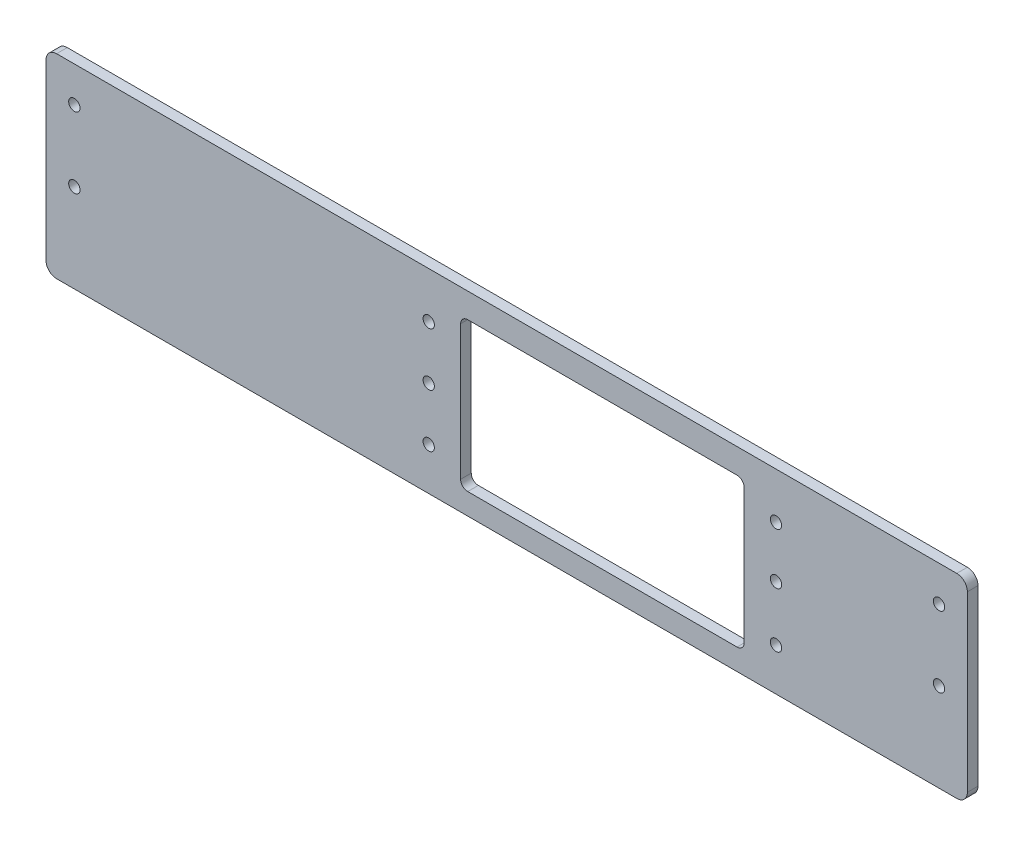
SolidWorks part; units mm, degrees
material "Thornel Mat VMA"
ref_plane "前视基准面" through (0, 0, 0) normal (0, 0, 1) x (1, 0, 0)
ref_plane "上视基准面" through (0, 0, 0) normal (0, 1, 0) x (1, 0, 0)
ref_plane "右视基准面" through (0, 0, 0) normal (1, 0, 0) x (0, 0, -1)
other "Configuration Table"
sketch "草图1" plane through (0, 0, 0) normal (0, 0, 1) x (1, 0, 0)
  line L1 (130, -27.5) -> (-130, -27.5)
  line L2 (130, -27.5) -> (130, 27.5)
  line L3 (130, 27.5) -> (-130, 27.5)
  line L4 (-130, -27.5) -> (-130, 27.5)
  line L5 (130, -27.5) -> (-130, 27.5) construction
  line L6 (130, 27.5) -> (-130, -27.5) construction
  point P0 (0, 0)
  dimension "D1" = 260
  dimension "D2" = 55
extrude "凸台-拉伸1" add sketch "草图1" along normal blind 3
fillet "圆角1" radius 3 4 edges at (130, 27.5, 1.5) (130, -27.5, 1.5) (-130, -27.5, 1.5) (-130, 27.5, 1.5)
sketch "草图2" plane through (0, 0, 3) normal (0, 0, 1) x (1, 0, 0)
  line L0 (-122, 27.5) -> (-122, -27.5) construction
  line L1 (127, 27.5) -> (-127, 27.5) construction
  line L2 (-127, -27.5) -> (127, -27.5) construction
  line L3 (122, 27.5) -> (122, -27.5) construction
  line L4 (130, -24.5) -> (130, 24.5) construction
  line L5 (-130, 24.5) -> (-130, -24.5) construction
  line L6 (0, 27.5) -> (0, -27.5) construction
  circle A0 centre (-122, 17.5) radius 1.6
  circle A1 centre (-122, -2.5) radius 1.6
  circle A2 centre (122, -2.5) radius 1.6
  circle A3 centre (122, 17.5) radius 1.6
  dimension "D3" = 20
  dimension "D4" = 10
  dimension "D5" = 3.2
  dimension "D1" = 8
  dimension "D2" = 8
extrude "切除-拉伸1" cut sketch "草图2" against normal blind 48
sketch "草图3" plane through (0, 0, 3) normal (0, 0, 1) x (1, 0, 0)
  line L0 (127, 27.5) -> (-127, 27.5) construction
  line L1 (-13, 20.5) -> (67, 20.5)
  line L2 (-13, 20.5) -> (-13, -21.5)
  line L3 (-13, -21.5) -> (67, -21.5)
  line L4 (67, 20.5) -> (67, -21.5)
  line L6 (130, -24.5) -> (130, 24.5) construction
  line L7 (27, 20.5) -> (27, -21.5) construction
  line L9 (76, -15.5) -> (-22, -15.5) construction
  line L10 (76, -15.5) -> (76, 14.5) construction
  line L11 (76, 14.5) -> (-22, 14.5) construction
  line L12 (-22, -15.5) -> (-22, 14.5) construction
  line L13 (76, -15.5) -> (-22, 14.5) construction
  line L14 (76, 14.5) -> (-22, -15.5) construction
  circle A0 centre (-22, 14.5) radius 1.6
  circle A1 centre (-22, -0.5) radius 1.6
  circle A2 centre (-22, -15.5) radius 1.6
  circle A3 centre (76, 14.5) radius 1.6
  circle A4 centre (76, 0) radius 1.6
  circle A5 centre (76, -15.5) radius 1.6
  point P10 (27, -0.5)
  dimension "D7" = 3.2
  dimension "D1" = 7
  dimension "D2" = 63
  dimension "D3" = 80
  dimension "D4" = 42
  dimension "D5" = 98
  dimension "D6" = 30
extrude "切除-拉伸2" cut sketch "草图3" against normal blind 327
fillet "圆角2" radius 2 4 edges at (67, 20.5, 1.5) (67, -21.5, 1.5) (-13, -21.5, 1.5) (-13, 20.5, 1.5)
